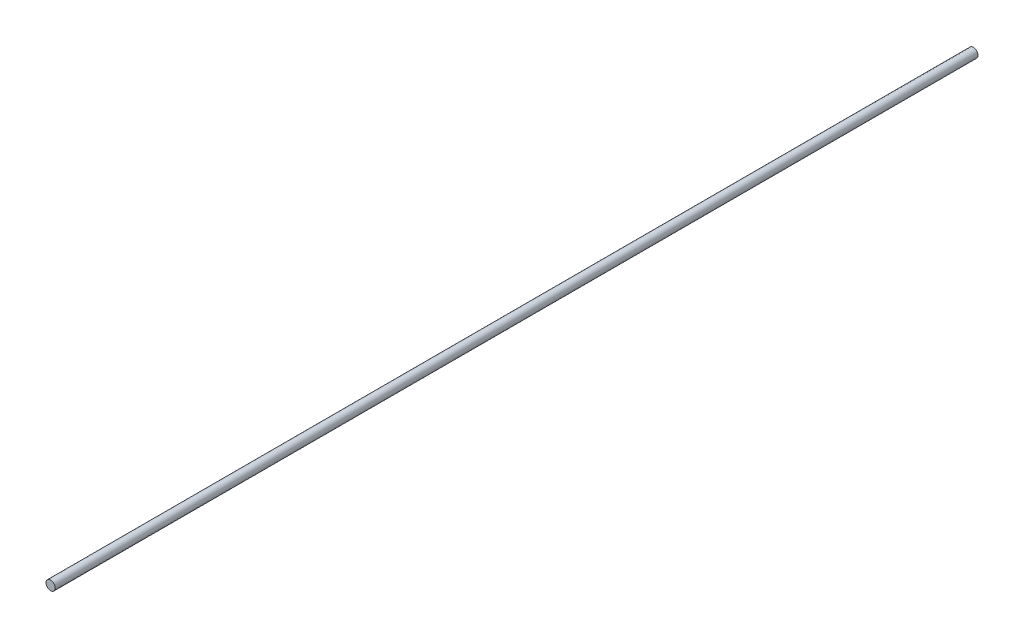
SolidWorks part; units mm, degrees
ref_plane "Front Plane" through (0, 0, 0) normal (0, 0, 1) x (1, 0, 0)
ref_plane "Top Plane" through (0, 0, 0) normal (0, 1, 0) x (1, 0, 0)
ref_plane "Right Plane" through (0, 0, 0) normal (1, 0, 0) x (0, 0, -1)
sketch "Sketch1" plane through (0, 0, 0) normal (0, 0, 1) x (1, 0, 0)
  circle A0 centre (0, 0) radius 25
  dimension "D1" = 50
extrude "Boss-Extrude1" add sketch "Sketch1" along normal blind 5000
